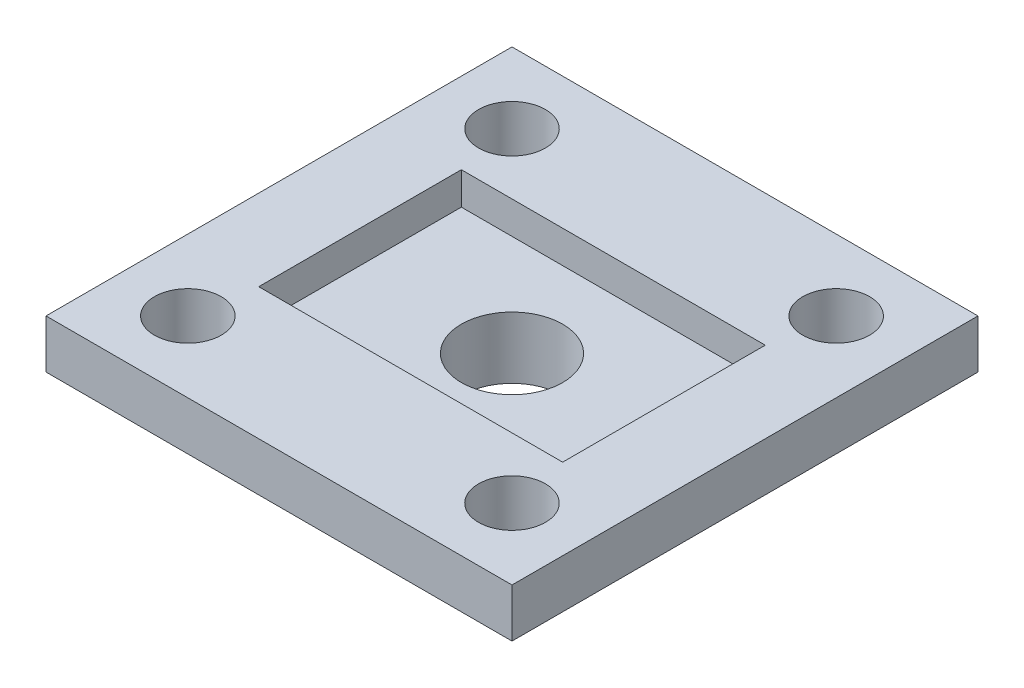
SolidWorks part; units mm, degrees
ref_plane "Front Plane" through (0, 0, 0) normal (0, 0, 1) x (1, 0, 0)
ref_plane "Top Plane" through (0, 0, 0) normal (0, 1, 0) x (1, 0, 0)
ref_plane "Right Plane" through (0, 0, 0) normal (1, 0, 0) x (0, 0, -1)
sketch "Sketch1" plane through (0, 0, 0) normal (0, 1, 0) x (1, 0, 0)
  line L0 (0, 11.5) -> (0, -11.5) construction
  line L1 (-11.5, -11.5) -> (11.5, -11.5)
  line L2 (-11.5, -11.5) -> (-11.5, 11.5)
  line L3 (-11.5, 11.5) -> (11.5, 11.5)
  line L4 (11.5, -11.5) -> (11.5, 11.5)
  line L5 (-11.5, -11.5) -> (11.5, 11.5) construction
  line L6 (-11.5, 11.5) -> (11.5, -11.5) construction
  circle A0 centre (-8, 8) radius 1.65
  circle A1 centre (8, -8) radius 1.65
  circle A2 centre (-8, -8) radius 1.65
  circle A3 centre (8, 8) radius 1.65
  point P0 (0, 0)
  dimension "D3" = 3.3
  dimension "D4" = 8
  dimension "D1" = 23
  dimension "D2" = 23
extrude "Boss-Extrude1" add sketch "Sketch1" along normal blind 2.4
sketch "Sketch2" plane through (0, 2.4, 0) normal (0, 1, 0) x (1, 0, 0)
  circle A0 centre (0, 0) radius 2.5
  dimension "D1" = 5
extrude "Cut-Extrude1" cut sketch "Sketch2" against normal up to next
sketch "Sketch3" plane through (0, 2.4, 0) normal (0, 1, 0) x (1, 0, 0)
  line L0 (-11.5, 0) -> (11.5, 0) construction
  line L1 (-7.5, -5) -> (7.5, -5)
  line L2 (-7.5, -5) -> (-7.5, 5)
  line L3 (-7.5, 5) -> (7.5, 5)
  line L4 (7.5, -5) -> (7.5, 5)
  line L5 (-7.5, -5) -> (7.5, 5) construction
  line L6 (-7.5, 5) -> (7.5, -5) construction
  line L7 (-11.5, 11.5) -> (-11.5, -11.5) construction
  line L8 (11.5, -11.5) -> (11.5, 11.5) construction
  line L9 (0, 11.5) -> (0, -11.5) construction
  line L16 (11.5, 11.5) -> (-11.5, 11.5) construction
  line L17 (-11.5, -11.5) -> (11.5, -11.5) construction
  point P0 (0, 0)
  dimension "D1" = 15
  dimension "D2" = 10
extrude "Cut-Extrude2" cut sketch "Sketch3" against normal blind 1.6
sketch "Sketch4" plane through (0, 0, 0) normal (0, -1, 0) x (1, 0, 0)
  circle A0 centre (0, 0) radius 2.5
  circle A1 centre (0, 0) radius 3.5
  dimension "D1" = 5
  dimension "D2" = 7
extrude "Boss-Extrude2" add sketch "Sketch4" along normal blind 2.25
